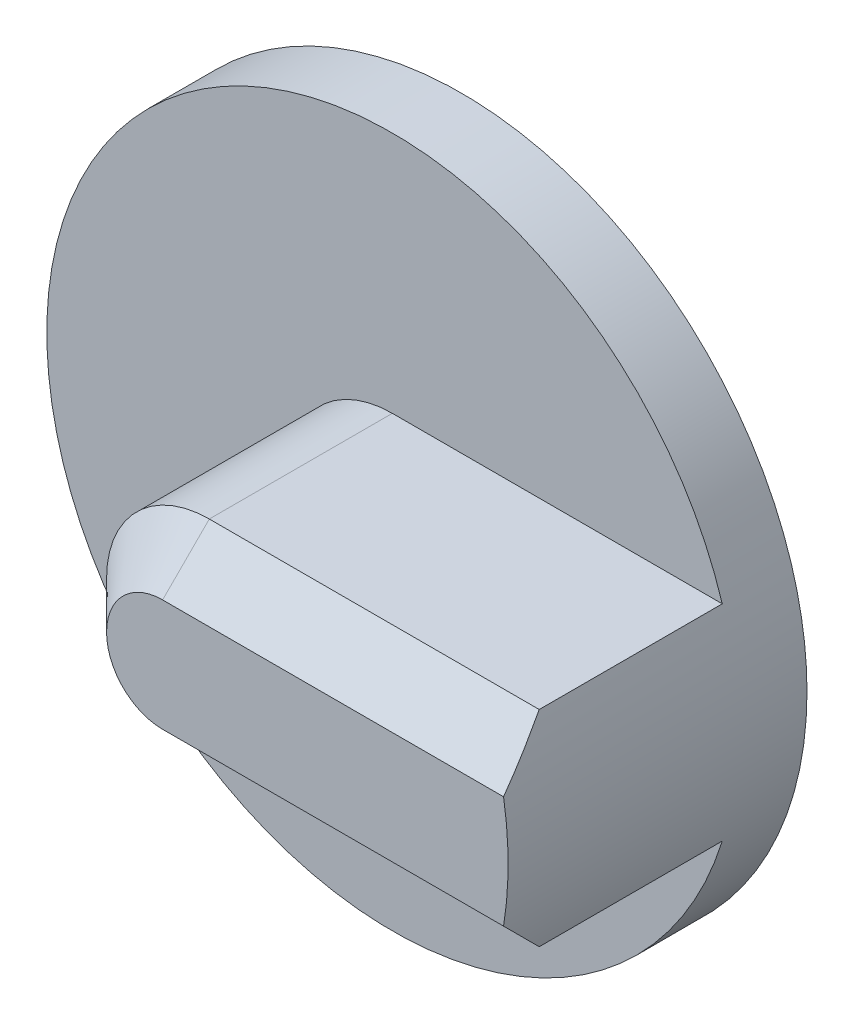
SolidWorks part; units mm, degrees
ref_plane "Front Plane" through (0, 0, 0) normal (0, 0, 1) x (1, 0, 0)
ref_plane "Top Plane" through (0, 0, 0) normal (0, 1, 0) x (1, 0, 0)
ref_plane "Right Plane" through (0, 0, 0) normal (1, 0, 0) x (0, 0, -1)
sketch "Sketch1" plane through (0, 0, 60) normal (0, 0, 1) x (1, 0, 0)
  circle A0 centre (0, 0) radius 37 construction
  circle A1 centre (0, 0) radius 37
extrude "Boss-Extrude1" add sketch "Sketch1" along normal up to surface (7.4 mm away)
sketch "Sketch2" plane through (0, 0, 67.4) normal (0, 0, 1) x (1, 0, 0)
  line L0 (0, 11) -> (35.327, 11)
  line L1 (0, -11) -> (35.327, -11)
  arc A0 (0, 11) -> (0, -11) centre (0, 0) ccw
  circle A1 centre (0, 0) radius 37 construction
  arc A2 (35.327, -11) -> (35.327, 11) centre (0, 0) ccw
  dimension "D1" = 22
extrude "Boss-Extrude2" add sketch "Sketch2" along normal offset from surface (24.6 mm away) 92
chamfer "Chamfer1" distance 5 angle 45 3 edges at (17.6635, 11, 92) (-11, 0, 92) (17.6635, -11, 92)
